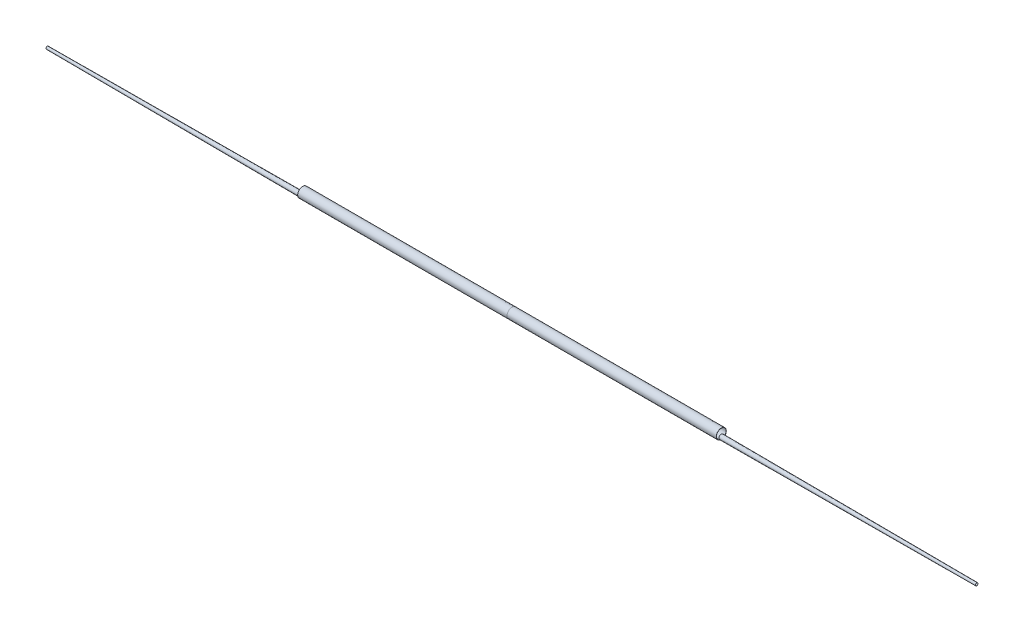
SolidWorks part; units mm, degrees
material "CARBON FIBERR"
ref_plane "Front Plane" through (0, 0, 0) normal (0, 0, 1) x (1, 0, 0)
ref_plane "Top Plane" through (0, 0, 0) normal (0, 1, 0) x (1, 0, 0)
ref_plane "Right Plane" through (0, 0, 0) normal (1, 0, 0) x (0, 0, -1)
sketch "Sketch1" plane through (0, 0, 0) normal (1, 0, 0) x (0, 0, -1)
  line L0 (0, 0) -> (363.728, 0) construction
  line L1 (363.728, 0) -> (363.728, 24.544) construction
  circle A0 centre (363.728, 24.544) radius 17.907
  dimension "D3" = 35.814
  dimension "D1" = 363.728
  dimension "D2" = 24.544
extrude "Uniform Tube" add sketch "Sketch1" along normal blind 749.3
sketch "Sketch2" plane through (749.3, 0, 0) normal (1, 0, 0) x (0, 0, -1)
  line L0 (363.728, 42.451) -> (363.728, 6.637) construction
  circle A0 centre (363.728, 15.0825) radius 8.4455
  circle A1 centre (363.728, 24.544) radius 17.907 construction
  dimension "D1" = 16.891
shell "Uniform Tube Shell" thickness 0.762
ref_plane "Wingtip Plane" through (1663.7, 0, 0) normal (1, 0, 0) x (0, 0, -1)
sketch "Sketch3" plane through (1663.7, 0, 0) normal (1, 0, 0) x (0, 0, -1)
  circle A0 centre (363.728, 15.0825) radius 4.6609
  dimension "D1" = 9.3218
loft "Tapered Tube" add profiles "Sketch3", "Sketch2"
shell "Tapered Tube Shell" thickness 0.254
mirror "Mirror2" about plane through (0, 0, 0) normal (1, 0, 0) of bodies 102 101
